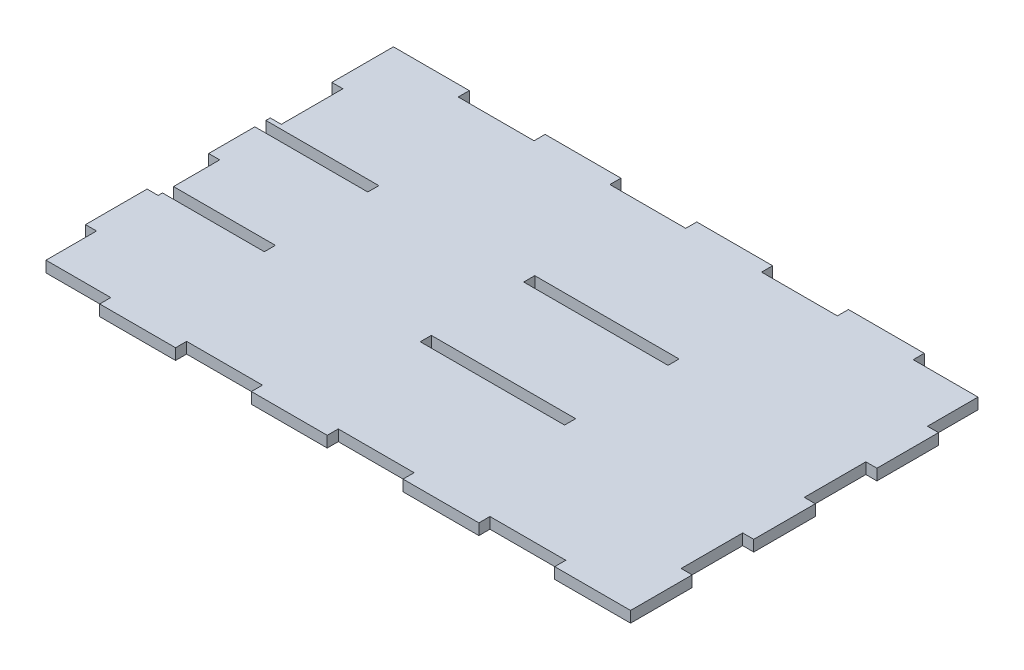
SolidWorks part; units mm, degrees
ref_plane "Front Plane" through (0, 0, 0) normal (0, 0, 1) x (1, 0, 0)
ref_plane "Top Plane" through (0, 0, 0) normal (0, 1, 0) x (1, 0, 0)
ref_plane "Right Plane" through (0, 0, 0) normal (1, 0, 0) x (0, 0, -1)
sketch "Sketch1" plane through (0, 0, 0) normal (0, 1, 0) x (1, 0, 0)
  line L0 (-131.9367, 77.9907) -> (-131.9367, -74.4093)
  line L5 (118.2533, 77.9907) -> (118.2533, -74.4093)
  line L6 (-131.9367, 77.9907) -> (118.2533, -74.4093) construction
  line L120 (118.2533, 77.9907) -> (-131.9367, 77.9907)
  line L123 (118.2533, -74.4093) -> (-131.9367, -74.4093)
  line L145 (118.2533, 77.9907) -> (113.694, 77.9907)
  line L146 (118.2533, 77.9907) -> (118.2533, 52.5907)
  line L147 (118.2533, 52.5907) -> (113.694, 52.5907)
  line L148 (113.694, 77.9907) -> (113.694, 52.5907)
  line L150 (113.694, 52.5907) -> (118.2533, 52.5907) construction
  line L151 (113.694, 52.5907) -> (113.694, 27.1907) construction
  line L152 (113.694, 27.1907) -> (118.2533, 27.1907) construction
  line L153 (118.2533, 52.5907) -> (118.2533, 27.1907) construction
  line L155 (113.694, 27.1907) -> (118.2533, 27.1907)
  line L156 (113.694, 27.1907) -> (113.694, 1.7907)
  line L157 (113.694, 1.7907) -> (118.2533, 1.7907)
  line L158 (118.2533, 27.1907) -> (118.2533, 1.7907)
  line L160 (113.694, 1.7907) -> (118.2533, 1.7907) construction
  line L161 (113.694, 1.7907) -> (113.694, -23.6093) construction
  line L162 (113.694, -23.6093) -> (118.2533, -23.6093) construction
  line L163 (118.2533, 1.7907) -> (118.2533, -23.6093) construction
  line L165 (113.694, -23.6093) -> (118.2533, -23.6093)
  line L166 (113.694, -23.6093) -> (113.694, -49.0093)
  line L167 (113.694, -49.0093) -> (118.2533, -49.0093)
  line L168 (118.2533, -23.6093) -> (118.2533, -49.0093)
  line L170 (113.694, -49.0093) -> (118.2533, -49.0093) construction
  line L171 (113.694, -49.0093) -> (113.694, -74.4093) construction
  line L172 (113.694, -74.4093) -> (118.2533, -74.4093) construction
  line L173 (118.2533, -49.0093) -> (118.2533, -74.4093) construction
  line L175 (-131.9367, -74.4093) -> (-100.663, -74.4093)
  line L176 (-131.9367, -74.4093) -> (-131.9367, -69.85)
  line L177 (-131.9367, -69.85) -> (-100.663, -69.85)
  line L178 (-100.663, -74.4093) -> (-100.663, -69.85)
  line L180 (-100.663, -69.85) -> (-69.3892, -69.85) construction
  line L181 (-100.663, -69.85) -> (-100.663, -74.4093) construction
  line L182 (-100.663, -74.4093) -> (-69.3892, -74.4093) construction
  line L183 (-69.3892, -69.85) -> (-69.3892, -74.4093) construction
  line L185 (-69.3892, -69.85) -> (-38.1155, -69.85)
  line L186 (-69.3892, -69.85) -> (-69.3892, -74.4093)
  line L187 (-69.3892, -74.4093) -> (-38.1155, -74.4093)
  line L188 (-38.1155, -69.85) -> (-38.1155, -74.4093)
  line L189 (-131.9367, -74.4093) -> (-131.9367, -49.0093)
  line L190 (-38.1155, -69.85) -> (-6.8417, -69.85) construction
  line L191 (-38.1155, -69.85) -> (-38.1155, -74.4093) construction
  line L192 (-38.1155, -74.4093) -> (-6.8417, -74.4093) construction
  line L193 (-6.8417, -69.85) -> (-6.8417, -74.4093) construction
  line L194 (-6.8417, -69.85) -> (24.432, -69.85)
  line L195 (-6.8417, -69.85) -> (-6.8417, -74.4093)
  line L196 (-6.8417, -74.4093) -> (24.432, -74.4093)
  line L197 (24.432, -69.85) -> (24.432, -74.4093)
  line L198 (24.432, -69.85) -> (55.7058, -69.85) construction
  line L199 (24.432, -69.85) -> (24.432, -74.4093) construction
  line L200 (24.432, -74.4093) -> (55.7058, -74.4093) construction
  line L201 (55.7058, -69.85) -> (55.7058, -74.4093) construction
  line L202 (55.7058, -69.85) -> (86.9795, -69.85)
  line L203 (55.7058, -69.85) -> (55.7058, -74.4093)
  line L204 (55.7058, -74.4093) -> (86.9795, -74.4093)
  line L205 (86.9795, -69.85) -> (86.9795, -74.4093)
  line L206 (86.9795, -69.85) -> (118.2533, -69.85) construction
  line L207 (86.9795, -69.85) -> (86.9795, -74.4093) construction
  line L208 (86.9795, -74.4093) -> (118.2533, -74.4093) construction
  line L209 (118.2533, -69.85) -> (118.2533, -74.4093) construction
  line L210 (-131.9367, -74.4093) -> (-127.3774, -74.4093)
  line L211 (-127.3774, -74.4093) -> (-127.3774, -49.0093)
  line L212 (-131.9367, -49.0093) -> (-127.3774, -49.0093)
  line L213 (-127.3774, -23.6093) -> (-127.3774, 1.7907)
  line L214 (-127.3774, -23.6093) -> (-131.9367, -23.6093)
  line L215 (-131.9367, -23.6093) -> (-131.9367, 1.7907)
  line L216 (-127.3774, 1.7907) -> (-131.9367, 1.7907)
  line L217 (-127.3774, 27.1907) -> (-131.9367, 27.1907)
  line L218 (-127.3774, 27.1907) -> (-127.3774, 52.5907)
  line L219 (-127.3774, 52.5907) -> (-131.9367, 52.5907)
  line L220 (-131.9367, 27.1907) -> (-131.9367, 52.5907)
  line L221 (118.2533, 77.9907) -> (118.2533, 73.4314)
  line L222 (118.2533, 77.9907) -> (86.9795, 77.9907)
  line L223 (86.9795, 77.9907) -> (86.9795, 73.4314)
  line L224 (118.2533, 73.4314) -> (86.9795, 73.4314)
  line L225 (55.7058, 73.4314) -> (55.7058, 77.9907)
  line L226 (55.7058, 73.4314) -> (24.432, 73.4314)
  line L227 (24.432, 73.4314) -> (24.432, 77.9907)
  line L228 (55.7058, 77.9907) -> (24.432, 77.9907)
  line L229 (-6.8417, 73.4314) -> (-6.8417, 77.9907)
  line L230 (-6.8417, 73.4314) -> (-38.1155, 73.4314)
  line L231 (-38.1155, 73.4314) -> (-38.1155, 77.9907)
  line L232 (-6.8417, 77.9907) -> (-38.1155, 77.9907)
  line L233 (-69.3892, 73.4314) -> (-69.3892, 77.9907)
  line L234 (-69.3892, 73.4314) -> (-100.663, 73.4314)
  line L235 (-100.663, 73.4314) -> (-100.663, 77.9907)
  line L236 (-69.3892, 77.9907) -> (-100.663, 77.9907)
  line L237 (118.2533, 77.9907) -> (-131.9367, -74.4093) construction
  line L238 (-6.8417, 1.7907) -> (-6.8417, 20.8407) construction
  line L239 (-21.0686, -17.2593) -> (38.4493, -17.2593)
  line L240 (-6.8417, 20.8407) -> (-131.9367, 20.8407) construction
  line L241 (-6.8417, 20.8407) -> (-6.8417, 1.7907) construction
  line L242 (-6.8417, 1.7907) -> (-131.9367, 1.7907) construction
  line L243 (-131.9367, 20.8407) -> (-131.9367, 1.7907) construction
  line L244 (-6.8417, 20.8407) -> (118.2533, 20.8407) construction
  line L245 (-6.8417, 20.8407) -> (-6.8417, 1.7907) construction
  line L246 (-6.8417, 1.7907) -> (118.2533, 1.7907) construction
  line L247 (118.2533, 20.8407) -> (118.2533, 1.7907) construction
  line L248 (-6.8417, 1.7907) -> (-131.9367, 1.7907) construction
  line L249 (-6.8417, 1.7907) -> (-6.8417, -17.2593) construction
  line L250 (-6.8417, -17.2593) -> (-131.9367, -17.2593) construction
  line L251 (-131.9367, 1.7907) -> (-131.9367, -17.2593) construction
  line L252 (-6.8417, -17.2593) -> (118.2533, -17.2593) construction
  line L253 (-6.8417, -17.2593) -> (-6.8417, 1.7907) construction
  line L254 (-6.8417, 1.7907) -> (118.2533, 1.7907) construction
  line L255 (118.2533, -17.2593) -> (118.2533, 1.7907) construction
  line L256 (-131.9367, 20.8407) -> (-85.3686, 20.8407)
  line L257 (-131.9367, 20.8407) -> (-131.9367, 25.4)
  line L258 (-131.9367, 25.4) -> (-85.3686, 25.4)
  line L259 (-85.3686, 20.8407) -> (-85.3686, 25.4)
  line L260 (-85.3686, 25.4) -> (-21.0686, 25.4) construction
  line L261 (-85.3686, 25.4) -> (-85.3686, 20.8407) construction
  line L262 (-85.3686, 20.8407) -> (-21.0686, 20.8407) construction
  line L263 (-21.0686, 25.4) -> (-21.0686, 20.8407) construction
  line L264 (-21.0686, 25.4) -> (38.4493, 25.4)
  line L265 (-21.0686, 25.4) -> (-21.0686, 20.8407)
  line L266 (-21.0686, 20.8407) -> (38.4493, 20.8407)
  line L267 (38.4493, 25.4) -> (38.4493, 20.8407)
  line L268 (38.4493, 25.4) -> (118.2533, 25.4) construction
  line L269 (38.4493, 25.4) -> (38.4493, 20.8407) construction
  line L270 (38.4493, 20.8407) -> (118.2533, 20.8407) construction
  line L271 (118.2533, 25.4) -> (118.2533, 20.8407) construction
  line L272 (38.4493, -21.8186) -> (38.4493, -17.2593)
  line L273 (-21.0686, -21.8186) -> (38.4493, -21.8186)
  line L274 (-21.0686, -21.8186) -> (-21.0686, -17.2593)
  line L275 (-131.9367, -21.8186) -> (-85.3686, -21.8186)
  line L276 (-85.3686, -17.2593) -> (-85.3686, -21.8186)
  line L277 (-131.9367, -17.2593) -> (-131.9367, -21.8186)
  line L278 (-131.9367, -17.2593) -> (-85.3686, -17.2593)
  point P45 (-6.8417, 1.7907)
  point P64 (-6.8417, 1.7907)
  dimension "D1" = 250.19
  dimension "D2" = 152.4
  dimension "D3" = 4.5593
  dimension "D4" = 4.5593
  dimension "D5" = 19.05
  dimension "D8" = 4.5593
  dimension "D6" = 2
extrude "Boss-Extrude1" add sketch "Sketch1" along normal blind 4.5593
equation "\"material_width\" = 0.1795"
equation "\"head_height\" = 2.0"
equation "\"neck_height\" = \"max32_width\""
equation "\"washer_height\" = 0.1"
equation "\"wall_length\" = 3.5"
equation "\"wall_height\" = 1.5"
equation "\"extra_space\" = 0.25"
equation "\"arc_radius\" = \"wall_length\" + \"washer_height\" + \"neck_height\" + (\"head_height\"/2)"
equation "\"arc_wall_height\" = \"arc_radius\" + \"wall_length\" + \"extra_space\""
equation "\"foot_length\" = 1.0"
equation "\"peg_diameter\" = 0.2475"
equation "\"D1@Boss-Extrude1\"=\"material_width\""
equation "\"D1@Sketch1\"=\"arc_wall_height\" + \"foot_length\""
equation "\"D3@Sketch1\"=\"material_width\""
equation "\"D4@Sketch1\"=\"material_width\""
equation "\"D5@Sketch1\"=\"wall_height\"/2"
equation "\"D8@Sketch1\"=\"material_width\""
